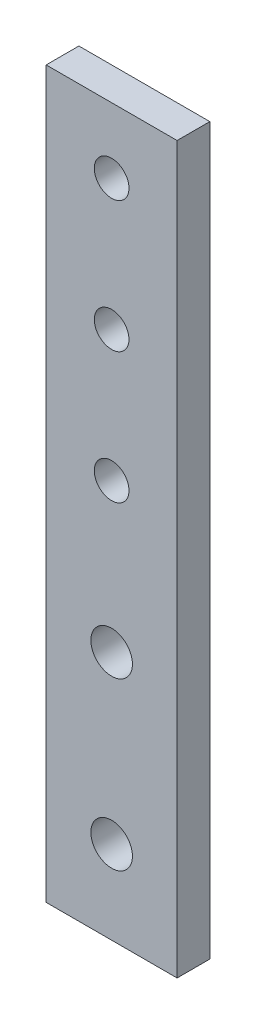
SolidWorks part; units mm, degrees
ref_plane "Front Plane" through (0, 0, 0) normal (0, 0, 1) x (1, 0, 0)
ref_plane "Top Plane" through (0, 0, 0) normal (0, 1, 0) x (1, 0, 0)
ref_plane "Right Plane" through (0, 0, 0) normal (1, 0, 0) x (0, 0, -1)
sketch "Sketch1" plane through (0, 0, 0) normal (0, 0, 1) x (1, 0, 0)
  line L1 (-3.4802, 75.833) -> (16.5198, 75.833)
  line L2 (-3.4802, 75.833) -> (-3.4802, -34.967)
  line L3 (-3.4802, -34.967) -> (16.5198, -34.967)
  line L4 (16.5198, 75.833) -> (16.5198, -34.967)
  dimension "D1" = 20
  dimension "D2" = 110.8
extrude "Boss-Extrude1" add sketch "Sketch1" along normal blind 5
sketch "Sketch2" plane through (0, 0, 5) normal (0, 0, 1) x (1, 0, 0)
  line L0 (6.5198, 65.833) -> (6.5198, 45.833)
  line L2 (16.5198, 75.833) -> (-3.4802, 75.833) construction
  line L3 (6.5198, 45.833) -> (6.5198, 25.833)
  line L4 (6.5198, -22.267) -> (6.5198, 3.133)
  line L5 (-3.4802, -34.967) -> (16.5198, -34.967) construction
  point P2 (6.5198, 75.833)
  dimension "D1" = 0
  dimension "D2" = 10
  dimension "D3" = 20
  dimension "D4" = 20
  dimension "D5" = 12.7
  dimension "D6" = 25.4
hole_wizard "M5 Clearance Hole1" positions "Sketch3" profile "Sketch4" hole size "M5" standard "ANSI Metric" end condition through all
sketch "Sketch3" plane through (0, 0, 5) normal (0, 0, 1) x (1, 0, 0)
  point P0 (6.5198, 65.833)
  point P3 (6.5198, 45.833)
  point P6 (6.5198, 25.833)
sketch "Sketch4" plane through (6.5198, 65.833, 5) normal (1, 0, 0) x (0, -1, 0)
  line L0 (0, 0) -> (0, 5)
  line L1 (0, 5) -> (2.65, 5)
  line L2 (2.65, 5) -> (2.65, 0)
  line L5 (2.65, 0) -> (0, 0)
  line L11 (0, -6.35) -> (0, 107.95) construction
  dimension "Thru Hole Dia." = 5.3
  dimension "Thru Hole Depth" = 5
hole_wizard "1/4 (0.25) Diameter Hole1" positions "Sketch5" profile "Sketch6" hole size "1/4" standard "ANSI Inch" end condition through all
sketch "Sketch5" plane through (0, 0, 5) normal (0, 0, 1) x (1, 0, 0)
  point P0 (6.5198, 3.133)
  point P3 (6.5198, -22.267)
sketch "Sketch6" plane through (6.5198, 3.133, 5) normal (1, 0, 0) x (0, -1, 0)
  line L0 (0, 0) -> (0, 5)
  line L1 (0, 5) -> (3.175, 5)
  line L2 (3.175, 5) -> (3.175, 0)
  line L5 (3.175, 0) -> (0, 0)
  line L11 (0, -6.35) -> (0, 107.95) construction
  dimension "Thru Hole Dia." = 6.35
  dimension "Thru Hole Depth" = 5
equation "\"D2@Sketch1\"=60 + 25.4*2"
